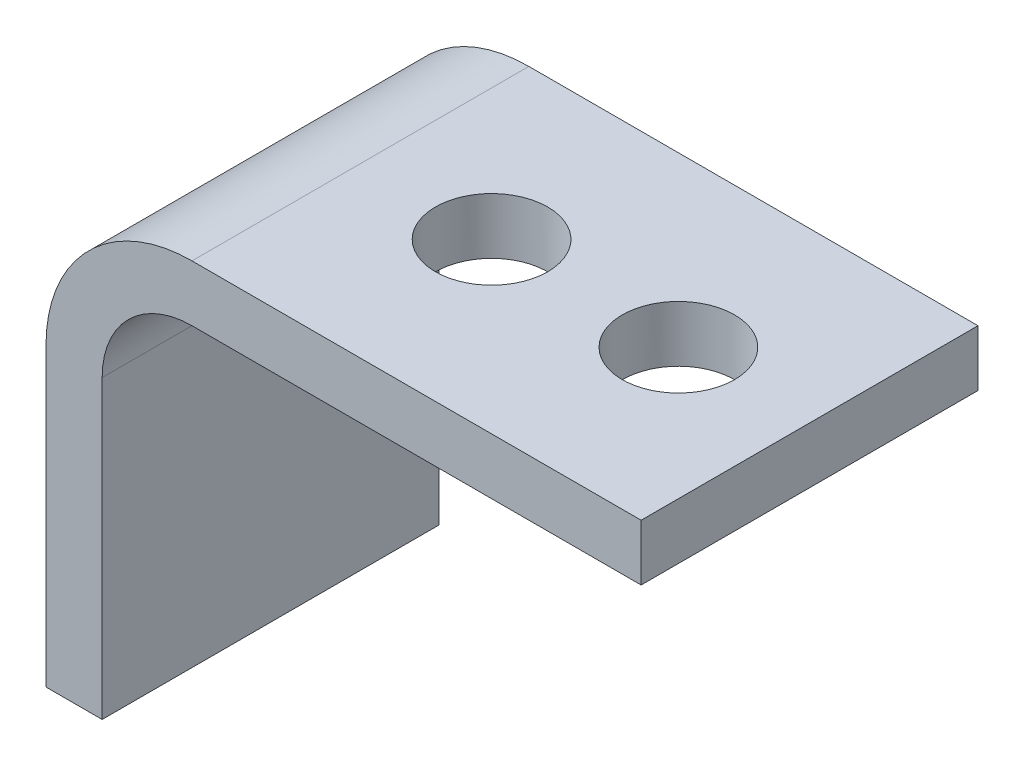
SolidWorks part; units mm, degrees
material "6061 Alloy"
ref_plane "Front Plane" through (0, 0, 0) normal (0, 0, 1) x (1, 0, 0)
ref_plane "Top Plane" through (0, 0, 0) normal (0, 1, 0) x (1, 0, 0)
ref_plane "Right Plane" through (0, 0, 0) normal (1, 0, 0) x (0, 0, -1)
sketch "Sketch1" plane through (0, 0, 0) normal (0, 0, 1) x (1, 0, 0)
  line L0 (0, 0) -> (0, 8.3725)
  line L1 (2.54, 10.9125) -> (15.24, 10.9125)
  line L2 (-1.5875, 0) -> (-1.5875, 8.3725)
  line L3 (2.54, 12.5) -> (15.24, 12.5)
  line L4 (-1.5875, 0) -> (0, 0)
  line L5 (15.24, 10.9125) -> (15.24, 12.5)
  arc A0 (0, 8.3725) -> (2.54, 10.9125) centre (2.54, 8.3725) cw
  arc A1 (-1.5875, 8.3725) -> (2.54, 12.5) centre (2.54, 8.3725) cw
  dimension "D1" = 2.54
  dimension "D2" = 12.7
  dimension "D3" = 12.5
  dimension "D4" = 1.5875
extrude "Boss-Extrude1" add sketch "Sketch1" along normal blind 9.525
sketch "Sketch2" plane through (0, 0, 0) normal (1, 0, 0) x (0, 0, -1)
  line L4 (0, 0) -> (0, 8.3725)
  line L5 (0, 8.3725) -> (-9.525, 8.3725)
  line L6 (-9.525, 8.3725) -> (-9.525, 0)
  line L7 (-9.525, 0) -> (0, 0)
  line L8 (0, 0) -> (0, 8.3725)
  line L9 (0, 8.3725) -> (-9.525, 8.3725)
  line L10 (-9.525, 8.3725) -> (-9.525, 0)
  line L11 (-9.525, 0) -> (0, 0)
  circle A2 centre (-2.25, 6.277) radius 2.0955
  circle A3 centre (-2.25, 6.277) radius 0.75
  dimension "D2" = 1.5
  dimension "D3" = 2.25
  dimension "D1" = 0
extrude "Cut-Extrude1" cut sketch "Sketch2" against normal up to next (1.5875 mm away) from surface at 0 contours A3 starting at face at (0, 4.1863, 4.7625)
sketch "Sketch3" plane through (0, 10.9125, 0) normal (0, -1, 0) x (1, 0, 0)
  line L0 (15.24, 4.7625) -> (2.54, 4.7625) construction
  line L1 (15.24, 9.525) -> (15.24, 0) construction
  line L2 (2.54, 9.525) -> (2.54, 0) construction
  circle A0 centre (6.2484, 4.7625) radius 1.5875
  circle A1 centre (11.5316, 4.7625) radius 1.5875
  dimension "D1" = 3.7084
  dimension "D3" = 5.2832
  dimension "D2" = 3.7084
extrude "Cut-Extrude2" cut sketch "Sketch3" against normal blind 2.54 contours L0 A0 | L0 A0 | L0 A1 | L0 A1
